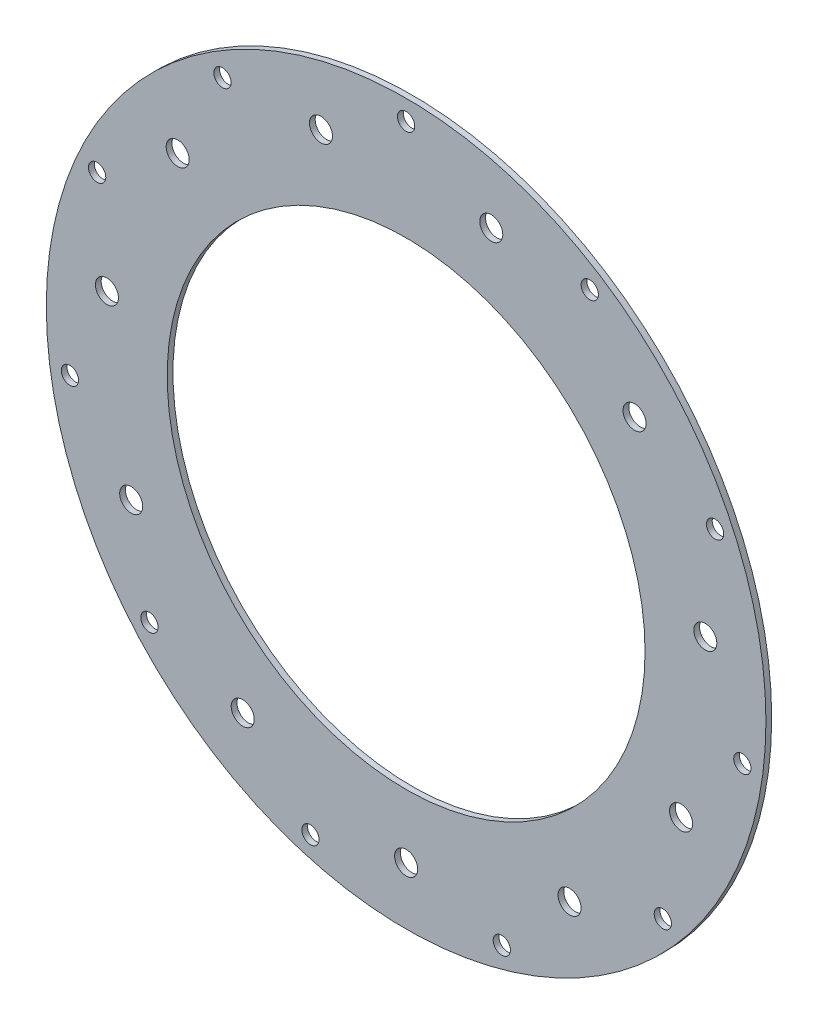
SolidWorks part; units mm, degrees
ref_plane "前视基准面" through (0, 0, 0) normal (0, 0, 1) x (1, 0, 0)
ref_plane "上视基准面" through (0, 0, 0) normal (0, 1, 0) x (1, 0, 0)
ref_plane "右视基准面" through (0, 0, 0) normal (1, 0, 0) x (0, 0, -1)
sketch "草图1" plane through (0, 0, 0) normal (0, 0, 1) x (1, 0, 0)
  line L0 (-28.3836, -44.1658) -> (0, -52.5) construction
  line L1 (-14.1918, -48.3329) -> (-20.9087, -71.2083) construction
  circle A0 centre (0, 0) radius 41.5
  circle A1 centre (0, 0) radius 62.5
  circle A2 centre (0, 0) radius 59 construction
  circle A19 centre (0, 0) radius 52.5 construction
  circle A20 centre (0, -52.5) radius 2
  circle A21 centre (-28.3836, -44.1658) radius 2
  circle A22 centre (-47.7557, -21.8093) radius 2
  circle A23 centre (-51.9656, 7.4715) radius 2
  circle A24 centre (-39.6769, 34.3802) radius 2
  circle A25 centre (-14.791, 50.3734) radius 2
  circle A26 centre (14.791, 50.3734) radius 2
  circle A27 centre (39.6769, 34.3802) radius 2
  circle A28 centre (51.9656, 7.4715) radius 2
  circle A29 centre (47.7557, -21.8093) radius 2
  circle A30 centre (28.3836, -44.1658) radius 2
  circle A31 centre (-16.6222, -56.6101) radius 1.5
  circle A32 centre (-44.5892, -38.6368) radius 1.5
  circle A33 centre (-58.3995, -8.3966) radius 1.5
  circle A34 centre (-53.6683, 24.5095) radius 1.5
  circle A35 centre (-31.8978, 49.634) radius 1.5
  circle A36 centre (0, 59) radius 1.5
  circle A37 centre (31.8978, 49.634) radius 1.5
  circle A38 centre (53.6683, 24.5095) radius 1.5
  circle A39 centre (58.3995, -8.3966) radius 1.5
  circle A40 centre (44.5892, -38.6368) radius 1.5
  circle A41 centre (16.6222, -56.6101) radius 1.5
  dimension "D1" = 83
  dimension "D2" = 125
  dimension "D3" = 118
  dimension "D4" = 3
  dimension "D6" = 105
  dimension "D7" = 4
  dimension "D8" = 11
  dimension "D5" = 11
extrude "凸台-拉伸1" add sketch "草图1" along normal blind 1
equation "\"52.5×2\"=96.9638"
